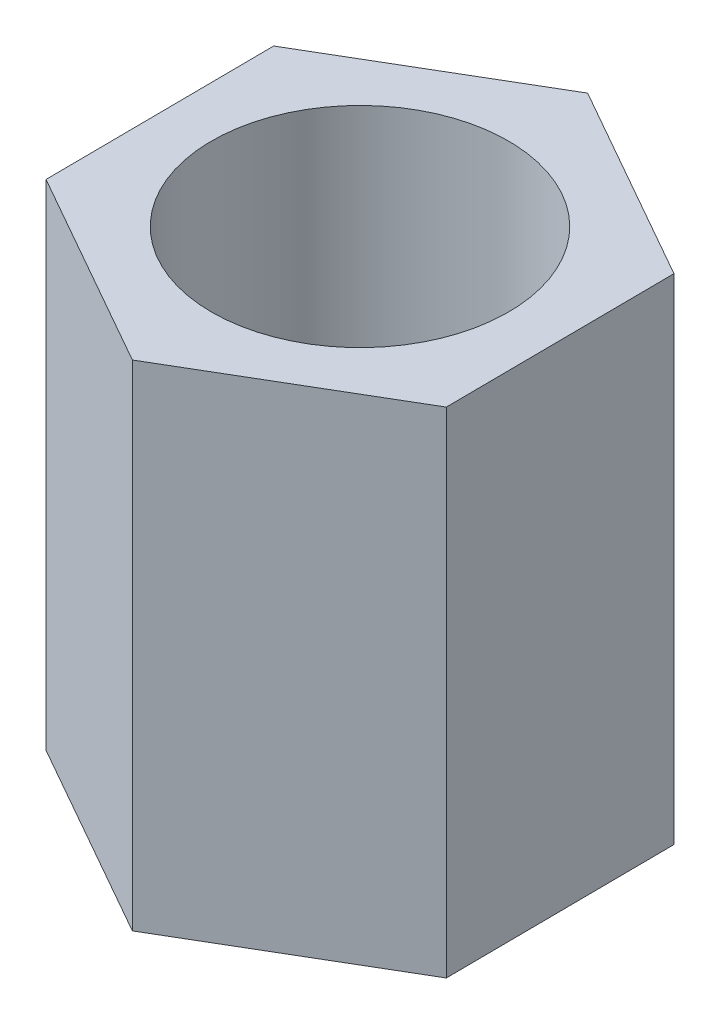
SolidWorks part; units mm, degrees
ref_plane "前视基准面" through (0, 0, 0) normal (0, 0, 1) x (1, 0, 0)
ref_plane "上视基准面" through (0, 0, 0) normal (0, 1, 0) x (1, 0, 0)
ref_plane "右视基准面" through (0, 0, 0) normal (1, 0, 0) x (0, 0, -1)
other "Configuration Table"
sketch "草图1" plane through (0, 0, 0) normal (0, 1, 0) x (1, 0, 0)
  line L1 (2, 1.1751) -> (-0.0176, 2.3196)
  line L2 (-0.0176, 2.3196) -> (-2.0176, 1.1445)
  line L3 (-2.0176, 1.1445) -> (-2, -1.1751)
  line L4 (-2, -1.1751) -> (0.0176, -2.3196)
  line L5 (0.0176, -2.3196) -> (2.0176, -1.1445)
  line L6 (2.0176, -1.1445) -> (2, 1.1751)
  circle A0 centre (0, 0) radius 1.5
  circle A1 centre (0, 0) radius 2.0089 construction
  dimension "D1" = 3
  dimension "D2" = 2
extrude "凸台-拉伸1" add sketch "草图1" along normal blind 5
